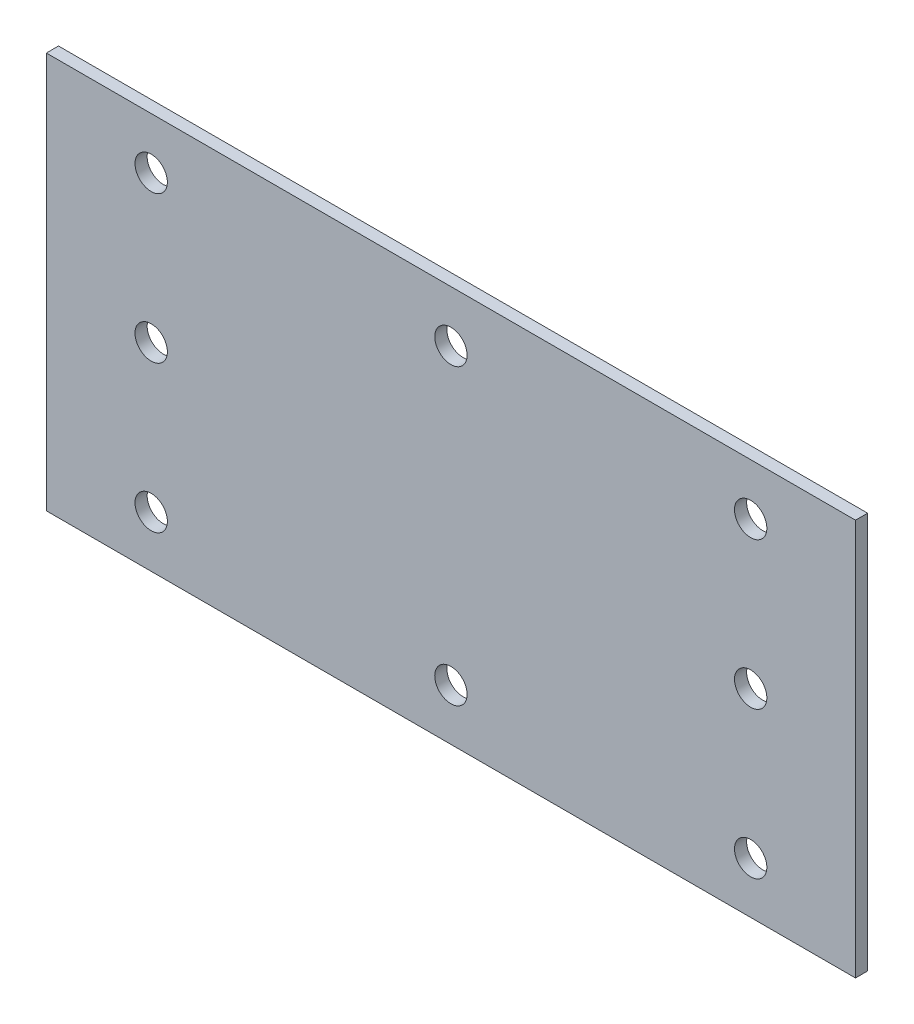
SolidWorks part; units mm, degrees
ref_plane "Front Plane" through (0, 0, 0) normal (0, 0, 1) x (1, 0, 0)
ref_plane "Top Plane" through (0, 0, 0) normal (0, 1, 0) x (1, 0, 0)
ref_plane "Right Plane" through (0, 0, 0) normal (1, 0, 0) x (0, 0, -1)
sketch "Sketch1" plane through (0, 0, 0) normal (0, 0, 1) x (1, 0, 0)
  line L5 (-126.4058, 64.6232) -> (73.5942, 64.6232)
  line L6 (-126.4058, 64.6232) -> (-126.4058, -33.3768)
  line L7 (-126.4058, -33.3768) -> (73.5942, -33.3768)
  line L8 (73.5942, 64.6232) -> (73.5942, -33.3768)
  circle A2 centre (47.6802, 51.9253) radius 4
  circle A3 centre (-100.4918, 51.9253) radius 4
  circle A4 centre (-100.4918, -20.679) radius 4
  circle A5 centre (47.6802, -20.679) radius 4
  circle A8 centre (-100.4918, 15.6232) radius 4
  circle A9 centre (47.6802, 15.6232) radius 4
  circle A10 centre (-26.4058, 51.9253) radius 4
  circle A11 centre (-26.4058, -20.679) radius 4
extrude "Boss-Extrude1" add sketch "Sketch1" along normal blind 3
